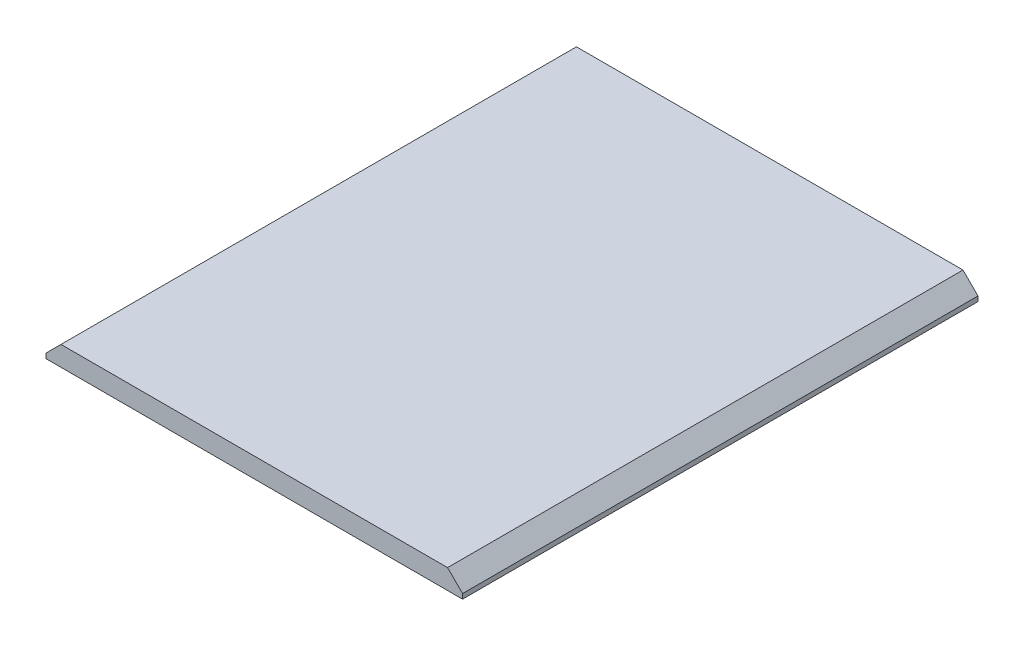
SolidWorks part; units mm, degrees
ref_plane "Front Plane" through (0, 0, 0) normal (0, 0, 1) x (1, 0, 0)
ref_plane "Top Plane" through (0, 0, 0) normal (0, 1, 0) x (1, 0, 0)
ref_plane "Right Plane" through (0, 0, 0) normal (1, 0, 0) x (0, 0, -1)
sketch "Sketch1" plane through (0, 0, 0) normal (0, 0, 1) x (1, 0, 0)
  line L0 (0, 2.65) -> (-2, 0.65)
  line L1 (0, 0) -> (25.8, 0)
  line L2 (0, 0) -> (0, 2.65)
  line L3 (0, 2.65) -> (25.8, 2.65)
  line L4 (25.8, 0) -> (25.8, 2.65)
  line L5 (-2, 0.65) -> (-2, 0)
  line L6 (-2, 0) -> (0, 0)
  dimension "D1" = 25.8
  dimension "D2" = 2.65
  dimension "D3" = 45
  dimension "D4" = 2
extrude "Boss-Extrude1" add sketch "Sketch1" along normal blind 68.8 contours L5 L6 L2 L0 | L1 L4 L3 L2
mirror "Mirror1" about plane through (25.8, 0, 68.8) normal (-1, 0, 0) of "Boss-Extrude1"
